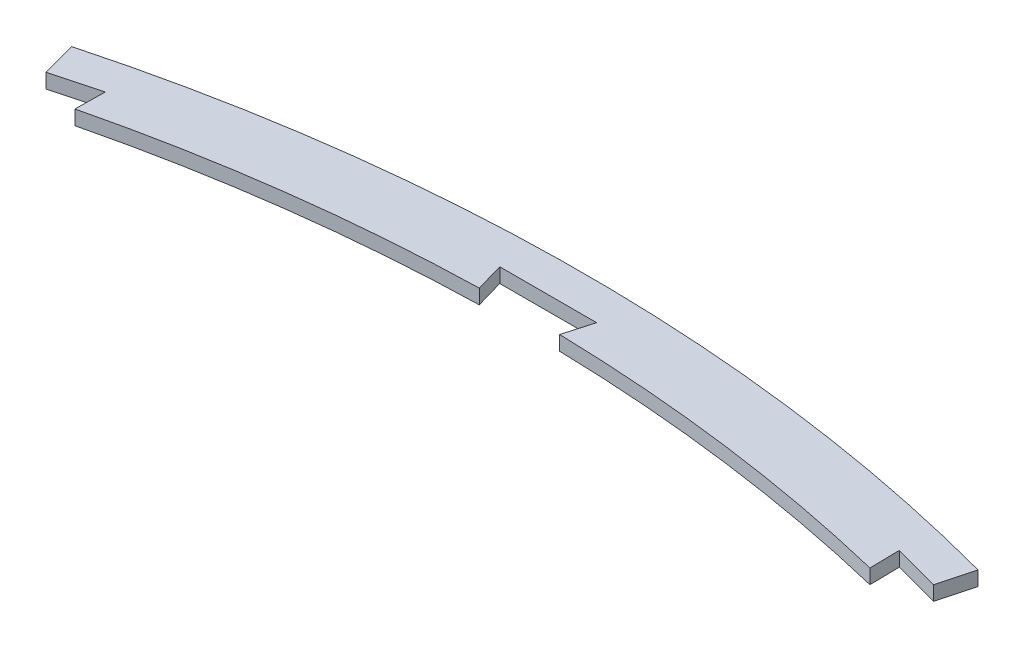
SolidWorks part; units mm, degrees
ref_plane "Front Plane" through (0, 0, 0) normal (0, 0, 1) x (1, 0, 0)
ref_plane "Top Plane" through (0, 0, 0) normal (0, 1, 0) x (1, 0, 0)
ref_plane "Right Plane" through (0, 0, 0) normal (1, 0, 0) x (0, 0, -1)
sketch "Sketch1" plane through (0, 0, 0) normal (0, 1, 0) x (1, 0, 0)
  line L0 (0, 0) -> (-280.8187, 1048.0295)
  line L1 (-280.8187, 1085) -> (280.8187, 1085) construction
  line L2 (-280.8187, 1085) -> (-280.8187, 785) construction
  line L3 (-280.8187, 785) -> (280.8187, 785) construction
  line L4 (280.8187, 1085) -> (280.8187, 785) construction
  line L5 (0, 0) -> (280.8187, 1048.0295)
  line L6 (0, 1020) -> (0, 0) construction
  line L7 (30, 1062.5) -> (-30, 1062.5)
  line L8 (-30, 1062.5) -> (-25, 1045)
  line L9 (955, 0) -> (1000, 0) construction
  line L10 (1000, 0) -> (1045, 0) construction
  line L11 (-24.9151, 1044.7029) -> (-25, 1045)
  line L12 (30, 1062.5) -> (25, 1045)
  line L13 (-274.9952, 1026.2962) -> (-246.0175, 1034.0608)
  line L14 (-246.0175, 1034.0608) -> (-246.3178, 1015.863)
  line L15 (-246.3178, 1015.863) -> (-246.3229, 1015.5541)
  line L16 (24.9151, 1044.7029) -> (25, 1045)
  line L17 (246.0175, 1034.0608) -> (246.3178, 1015.863)
  line L18 (274.9952, 1026.2962) -> (246.0175, 1034.0608)
  line L19 (246.3229, 1015.5541) -> (246.3178, 1015.863)
  circle A0 centre (0, 0) radius 1085
  circle A1 centre (0, 0) radius 1045
  circle A2 centre (0, 0) radius 955
  circle A3 centre (0, 0) radius 915
  circle A6 centre (0, 0) radius 1065 construction
  circle A7 centre (0, 0) radius 935 construction
  circle A9 centre (-227.4758, 906.9067) radius 4
  circle A10 centre (227.4758, 906.9067) radius 4
  circle A12 centre (0, 0) radius 1032.5 construction
  circle A15 centre (0, 0) radius 1000 construction
  point P12 (0, 785)
  point P28 (0, 1062.5)
  dimension "D3" = 40
  dimension "D4" = 40
  dimension "D5" = 20
  dimension "D6" = 20
  dimension "D7" = 170
  dimension "D8" = 2000
  dimension "D9" = 30
  dimension "D11" = 8
  dimension "D12" = 15
  dimension "D14" = 12.5
  dimension "D15" = 17.5
  dimension "D19" = 1062.5
  dimension "D20" = 17.5
  dimension "D21" = 25
  dimension "D10" = 25
  dimension "D16" = 1062.5
  dimension "D1" = 300
  dimension "D2" = 15
  dimension "D13" = 15
  dimension "D17" = 90
  dimension "D18" = 30
extrude "Boss-Extrude1" add sketch "Sketch1" along normal blind 9
